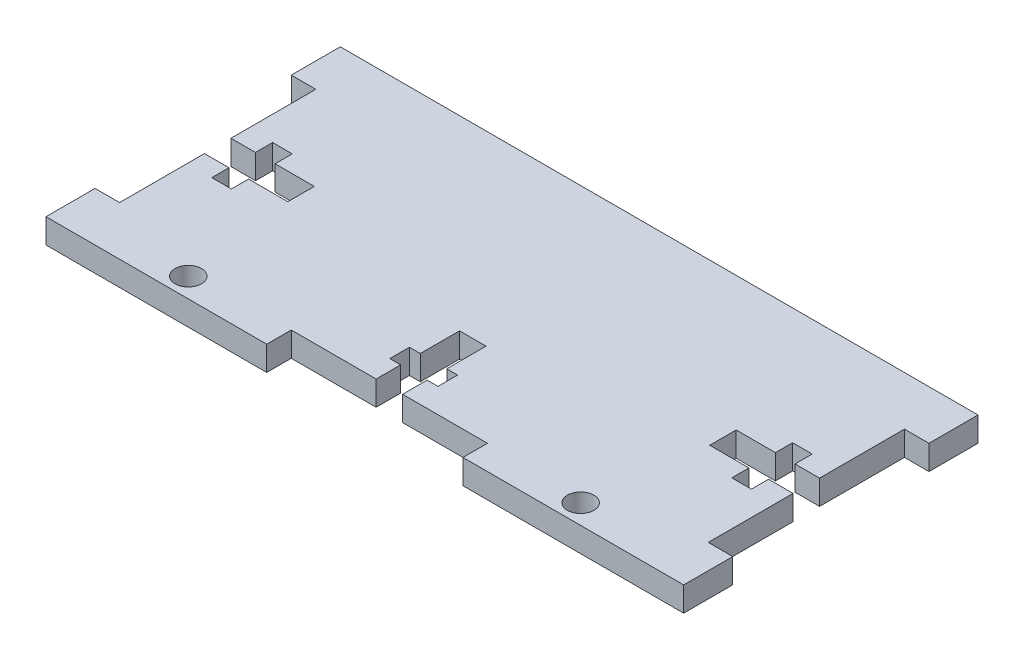
SolidWorks part; units mm, degrees
ref_plane "Front Plane" through (0, 0, 0) normal (0, 0, 1) x (1, 0, 0)
ref_plane "Top Plane" through (0, 0, 0) normal (0, 1, 0) x (1, 0, 0)
ref_plane "Right Plane" through (0, 0, 0) normal (1, 0, 0) x (0, 0, -1)
sketch "Sketch1" plane through (0, 0, 0) normal (0, 1, 0) x (1, 0, 0)
  line L0 (0, 0) -> (0, 34.925) construction
  line L1 (-12.7, 0) -> (12.7, 0)
  line L2 (12.7, 0) -> (12.7, -3.175)
  line L3 (12.7, -3.175) -> (41.275, -3.175)
  line L4 (41.275, -3.175) -> (41.275, 3.175)
  line L5 (41.275, 3.175) -> (38.1, 3.175)
  line L6 (38.1, 3.175) -> (38.1, 14.1605)
  line L7 (38.1, 28.575) -> (41.275, 28.575)
  line L8 (41.275, 28.575) -> (41.275, 34.925)
  line L9 (41.275, 34.925) -> (-41.275, 34.925)
  line L10 (38.1, 15.875) -> (27.305, 15.875) construction
  line L11 (38.1, 17.5895) -> (34.925, 17.5895)
  line L12 (34.925, 17.5895) -> (34.925, 19.812)
  line L13 (34.925, 19.812) -> (32.385, 19.812)
  line L14 (32.385, 19.812) -> (32.385, 17.5895)
  line L15 (32.385, 17.5895) -> (27.305, 17.5895)
  line L16 (27.305, 17.5895) -> (27.305, 14.1605)
  line L17 (32.385, 14.1605) -> (27.305, 14.1605)
  line L18 (32.385, 11.938) -> (32.385, 14.1605)
  line L19 (34.925, 11.938) -> (32.385, 11.938)
  line L20 (34.925, 14.1605) -> (34.925, 11.938)
  line L21 (38.1, 14.1605) -> (34.925, 14.1605)
  line L22 (38.1, 17.5895) -> (38.1, 28.575)
  line L23 (1.7145, 0) -> (1.7145, 3.175)
  line L24 (1.7145, 3.175) -> (3.1207, 3.175)
  line L25 (3.1207, 3.175) -> (3.1207, 5.715)
  line L26 (3.1207, 5.715) -> (1.7145, 5.715)
  line L27 (1.7145, 5.715) -> (1.7145, 10.795)
  line L28 (1.7145, 10.795) -> (-1.7145, 10.795)
  line L29 (25.4, -3.175) -> (25.4, -0.635) construction
  line L30 (-25.4, -3.175) -> (-25.4, -0.635) construction
  line L31 (-38.1, 15.875) -> (-27.305, 15.875) construction
  line L32 (-1.7145, 5.715) -> (-1.7145, 10.795)
  line L33 (-3.1207, 5.715) -> (-1.7145, 5.715)
  line L34 (-3.1207, 3.175) -> (-3.1207, 5.715)
  line L35 (-1.7145, 3.175) -> (-3.1207, 3.175)
  line L36 (-1.7145, 0) -> (-1.7145, 3.175)
  line L37 (-38.1, 17.5895) -> (-38.1, 28.575)
  line L38 (-38.1, 14.1605) -> (-34.925, 14.1605)
  line L39 (-34.925, 14.1605) -> (-34.925, 11.938)
  line L40 (-34.925, 11.938) -> (-32.385, 11.938)
  line L41 (-32.385, 11.938) -> (-32.385, 14.1605)
  line L42 (-32.385, 14.1605) -> (-27.305, 14.1605)
  line L43 (-27.305, 17.5895) -> (-27.305, 14.1605)
  line L44 (-32.385, 17.5895) -> (-27.305, 17.5895)
  line L45 (-32.385, 19.812) -> (-32.385, 17.5895)
  line L46 (-34.925, 19.812) -> (-32.385, 19.812)
  line L47 (-34.925, 17.5895) -> (-34.925, 19.812)
  line L48 (-38.1, 17.5895) -> (-34.925, 17.5895)
  line L49 (-41.275, 28.575) -> (-41.275, 34.925)
  line L50 (-38.1, 28.575) -> (-41.275, 28.575)
  line L51 (-38.1, 3.175) -> (-38.1, 14.1605)
  line L52 (-41.275, 3.175) -> (-38.1, 3.175)
  line L53 (-41.275, -3.175) -> (-41.275, 3.175)
  line L54 (-12.7, -3.175) -> (-41.275, -3.175)
  line L55 (-12.7, 0) -> (-12.7, -3.175)
  circle A0 centre (25.4, -0.635) radius 1.7145
  circle A1 centre (-25.4, -0.635) radius 1.7145
  point P41 (0, 10.795)
  dimension "D19" = 3.429
  dimension "D1" = 6.35
  dimension "D2" = 3.175
  dimension "D3" = 6.35
  dimension "D4" = 25.4
  dimension "D5" = 3.175
  dimension "D6" = 12.7
  dimension "D7" = 38.1
  dimension "D8" = 13.97
  dimension "D9" = 1.7145
  dimension "D10" = 3.937
  dimension "D11" = 2.54
  dimension "D12" = 3.175
  dimension "D13" = 1.7145
  dimension "D14" = 2.54
  dimension "D15" = 13.97
  dimension "D16" = 3.175
  dimension "D17" = 2.54
  dimension "D18" = 12.7
extrude "Boss-Extrude1" add sketch "Sketch1" along normal blind 3.175 contours L55 L1 L36 L35 L34 L33 L32 L28 L27 L26 L25 L24 L23 L2 L3 L4 L5 L6 L21 L20 L19 L18 L17 L16 L15 L14 L13 L12 L11 L22 L7 L8 L9 L49 L50 L37 L48 L47 L46 L45 L44 L43 L42 L41 L40 L39 L38 L51 L52 L53
